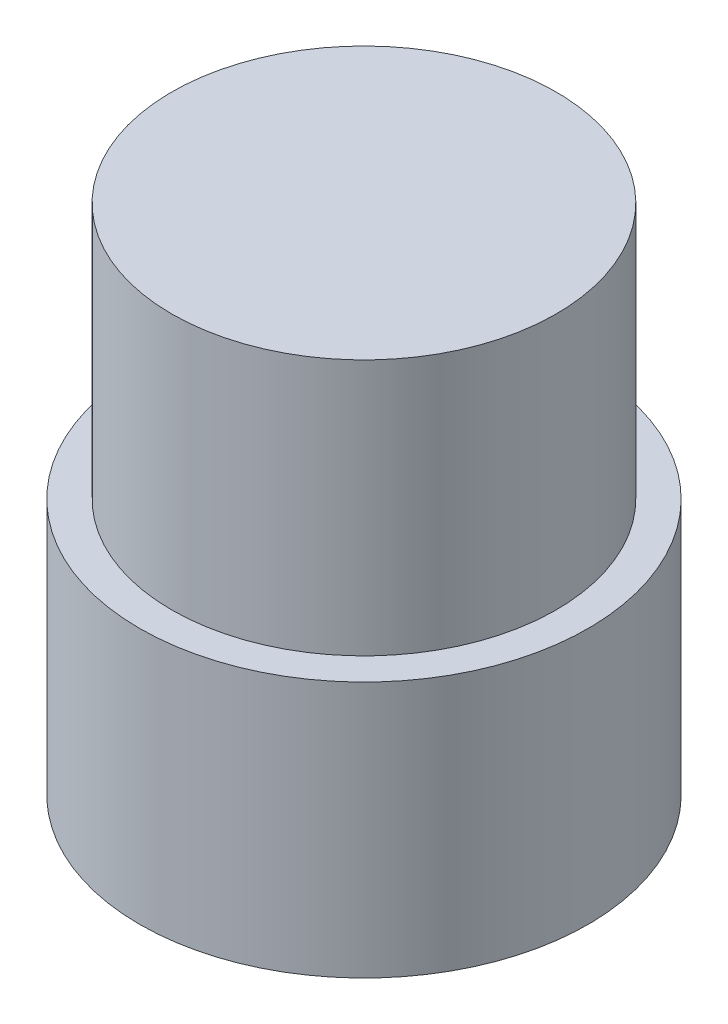
SolidWorks part; units mm, degrees
ref_plane "Front Plane" through (0, 0, 0) normal (0, 0, 1) x (1, 0, 0)
ref_plane "Top Plane" through (0, 0, 0) normal (0, 1, 0) x (1, 0, 0)
ref_plane "Right Plane" through (0, 0, 0) normal (1, 0, 0) x (0, 0, -1)
sketch "Sketch2" plane through (0, 0, 0) normal (0, 1, 0) x (1, 0, 0)
  circle A0 centre (0, 0) radius 1.75
  dimension "D1" = 3.5
extrude "Boss-Extrude1" add sketch "Sketch2" along normal blind 2
sketch "Sketch3" plane through (0, 2, 0) normal (0, 1, 0) x (1, 0, 0)
  circle A0 centre (0, 0) radius 1.5
  dimension "D1" = 3
extrude "Boss-Extrude2" add sketch "Sketch3" along normal blind 2
